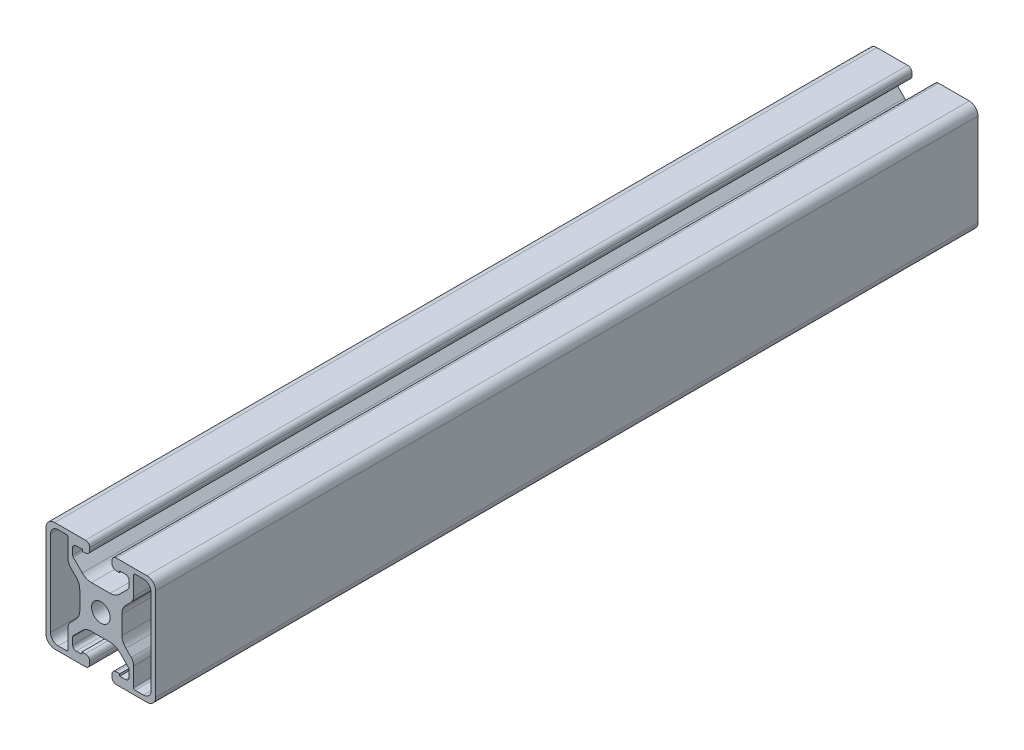
SolidWorks part; units mm, degrees
material "6105-T5 Aluminum"
ref_plane "Front Plane" through (0, 0, 0) normal (0, 0, 1) x (1, 0, 0)
ref_plane "Top Plane" through (0, 0, 0) normal (0, 1, 0) x (1, 0, 0)
ref_plane "Right Plane" through (0, 0, 0) normal (1, 0, 0) x (0, 0, -1)
sketch "Sketch1" plane through (0, 0, 0) normal (0, 0, 1) x (1, 0, 0)
  line L0 (0, 24.255) -> (0, -24.255) construction
  line L2 (-12.5645, -18.35) -> (-15.5575, -18.35)
  line L3 (-18.35, -15.5575) -> (-18.35, 15.5575)
  line L4 (-15.5575, 18.35) -> (-12.566, 18.35)
  line L5 (-10.9703, 8.6329) -> (-9.033, 6.6995)
  line L6 (-11.935, 17.7218) -> (-11.935, 10.9555)
  line L7 (-7.685, 3.2977) -> (-7.685, -3.508)
  line L8 (-9.1386, -6.7731) -> (-11.0739, -8.7045)
  line L9 (-11.935, -10.9555) -> (-11.935, -17.7218)
  line L10 (-24.8341, 0) -> (22.8703, 0) construction
  line L11 (3.4141, 7.7) -> (-3.4141, 7.7)
  line L12 (-6.7505, 9.0839) -> (-10.0407, 12.3673)
  line L13 (-10.285, 12.9795) -> (-10.285, 15.2929)
  line L14 (-9.015, 16.5629) -> (-6.7718, 16.5629)
  line L15 (-6.7718, 16.5629) -> (-6.7718, 15.94)
  line L16 (-6.7718, 15.94) -> (-5.6348, 15.94)
  line L17 (-4.06, 17.5148) -> (-4.06, 18.4252)
  line L18 (-5.6348, 20) -> (-13.0175, 20)
  line L19 (-13.0175, 20) -> (-16.825, 20)
  line L20 (-20, 16.825) -> (-20, -16.825)
  line L21 (-16.825, -20) -> (-13.0175, -20)
  line L22 (-13.0175, -20) -> (-5.6348, -20)
  line L23 (-4.06, -18.4252) -> (-4.06, -17.5148)
  line L24 (-5.6348, -15.94) -> (-6.8938, -15.94)
  line L25 (-6.8938, -15.94) -> (-6.8938, -16.7025)
  line L26 (-6.8938, -16.7025) -> (-9.015, -16.7025)
  line L27 (-10.285, -15.4325) -> (-10.285, -12.9481)
  line L28 (-10.024, -12.3188) -> (-6.7733, -9.0747)
  line L29 (-3.4312, -7.7) -> (3.4312, -7.7)
  line L30 (10.024, -12.3188) -> (6.7733, -9.0747)
  line L31 (10.285, -15.4325) -> (10.285, -12.9481)
  line L32 (6.8938, -16.7025) -> (9.015, -16.7025)
  line L33 (6.8938, -15.94) -> (6.8938, -16.7025)
  line L34 (5.6348, -15.94) -> (6.8938, -15.94)
  line L35 (4.06, -18.4252) -> (4.06, -17.5148)
  line L36 (13.0175, -20) -> (5.6348, -20)
  line L37 (16.825, -20) -> (13.0175, -20)
  line L38 (20, 16.825) -> (20, -16.825)
  line L39 (13.0175, 20) -> (16.825, 20)
  line L40 (5.6348, 20) -> (13.0175, 20)
  line L41 (4.06, 17.5148) -> (4.06, 18.4252)
  line L42 (6.7718, 15.94) -> (5.6348, 15.94)
  line L43 (6.7718, 16.5629) -> (6.7718, 15.94)
  line L44 (9.015, 16.5629) -> (6.7718, 16.5629)
  line L45 (10.285, 12.9795) -> (10.285, 15.2929)
  line L46 (6.7505, 9.0839) -> (10.0407, 12.3673)
  line L47 (11.935, -10.9555) -> (11.935, -17.7218)
  line L48 (9.1386, -6.7731) -> (11.0739, -8.7045)
  line L49 (7.685, 3.2977) -> (7.685, -3.508)
  line L50 (11.935, 17.7218) -> (11.935, 10.9555)
  line L51 (10.9703, 8.6329) -> (9.033, 6.6995)
  line L52 (15.5575, 18.35) -> (12.566, 18.35)
  line L53 (18.35, -15.5575) -> (18.35, 15.5575)
  line L54 (12.5645, -18.35) -> (15.5575, -18.35)
  circle A0 centre (0, 0) radius 3.4
  arc A1 (-12.5645, -18.35) -> (-11.935, -17.7218) centre (-12.57, -17.715) ccw
  arc A2 (-18.35, -15.5575) -> (-15.5575, -18.35) centre (-15.556, -15.556) ccw
  arc A3 (-15.5575, 18.35) -> (-18.35, 15.5575) centre (-15.556, 15.556) ccw
  arc A4 (-11.935, 17.7218) -> (-12.566, 18.35) centre (-12.57, 17.715) ccw
  arc A5 (-11.935, 10.9555) -> (-10.9703, 8.6329) centre (-8.7603, 10.9125) ccw
  arc A6 (-7.685, 3.2977) -> (-9.033, 6.6995) centre (-12.434, 3.3839) ccw
  arc A7 (-9.1386, -6.7731) -> (-7.685, -3.508) centre (-12.4322, -3.3507) ccw
  arc A8 (-11.0739, -8.7045) -> (-11.935, -10.9555) centre (-8.7609, -10.8795) ccw
  arc A9 (-6.7505, 9.0839) -> (-3.4141, 7.7) centre (-3.3992, 12.4498) ccw
  arc A10 (-10.285, 12.9795) -> (-10.0407, 12.3673) centre (-9.396, 12.9795) ccw
  arc A11 (-9.015, 16.5629) -> (-10.285, 15.2929) centre (-9.015, 15.2929) ccw
  arc A12 (-5.6348, 15.94) -> (-4.06, 17.5148) centre (-5.6348, 17.5148) ccw
  arc A13 (-4.06, 18.4252) -> (-5.6348, 20) centre (-5.6348, 18.4252) ccw
  arc A14 (-16.825, 20) -> (-20, 16.825) centre (-16.825, 16.825) ccw
  arc A15 (-20, -16.825) -> (-16.825, -20) centre (-16.825, -16.825) ccw
  arc A16 (-5.6348, -20) -> (-4.06, -18.4252) centre (-5.6348, -18.4252) ccw
  arc A17 (-4.06, -17.5148) -> (-5.6348, -15.94) centre (-5.6348, -17.5148) ccw
  arc A18 (-10.285, -15.4325) -> (-9.015, -16.7025) centre (-9.015, -15.4325) ccw
  arc A19 (-10.024, -12.3188) -> (-10.285, -12.9481) centre (-9.396, -12.9481) ccw
  arc A20 (-3.4312, -7.7) -> (-6.7733, -9.0747) centre (-3.4312, -12.4498) ccw
  arc A21 (3.4312, -7.7) -> (6.7733, -9.0747) centre (3.4312, -12.4498) cw
  arc A22 (10.024, -12.3188) -> (10.285, -12.9481) centre (9.396, -12.9481) cw
  arc A23 (10.285, -15.4325) -> (9.015, -16.7025) centre (9.015, -15.4325) cw
  arc A24 (4.06, -17.5148) -> (5.6348, -15.94) centre (5.6348, -17.5148) cw
  arc A25 (5.6348, -20) -> (4.06, -18.4252) centre (5.6348, -18.4252) cw
  arc A26 (20, -16.825) -> (16.825, -20) centre (16.825, -16.825) cw
  arc A27 (16.825, 20) -> (20, 16.825) centre (16.825, 16.825) cw
  arc A28 (4.06, 18.4252) -> (5.6348, 20) centre (5.6348, 18.4252) cw
  arc A29 (5.6348, 15.94) -> (4.06, 17.5148) centre (5.6348, 17.5148) cw
  arc A30 (9.015, 16.5629) -> (10.285, 15.2929) centre (9.015, 15.2929) cw
  arc A31 (10.285, 12.9795) -> (10.0407, 12.3673) centre (9.396, 12.9795) cw
  arc A32 (6.7505, 9.0839) -> (3.4141, 7.7) centre (3.3992, 12.4498) cw
  arc A33 (11.0739, -8.7045) -> (11.935, -10.9555) centre (8.7609, -10.8795) cw
  arc A34 (9.1386, -6.7731) -> (7.685, -3.508) centre (12.4322, -3.3507) cw
  arc A35 (7.685, 3.2977) -> (9.033, 6.6995) centre (12.434, 3.3839) cw
  arc A36 (11.935, 10.9555) -> (10.9703, 8.6329) centre (8.7603, 10.9125) cw
  arc A37 (11.935, 17.7218) -> (12.566, 18.35) centre (12.57, 17.715) cw
  arc A38 (15.5575, 18.35) -> (18.35, 15.5575) centre (15.556, 15.556) cw
  arc A39 (18.35, -15.5575) -> (15.5575, -18.35) centre (15.556, -15.556) cw
  arc A40 (12.5645, -18.35) -> (11.935, -17.7218) centre (12.57, -17.715) cw
  dimension "D6" = 6.8
  dimension "D1" = 1.65
  dimension "D2" = 12.3
  dimension "D3" = 8.12
  dimension "D4" = 40
  dimension "D5" = 20
  dimension "D7" = 1.65
  dimension "D8" = 3.3
  dimension "D9" = 15.37
  dimension "D10" = 20.57
  dimension "D11" = 4.06
  dimension "D12" = 1.65
extrude "Extrude1" add sketch "Sketch1" against normal blind 300
